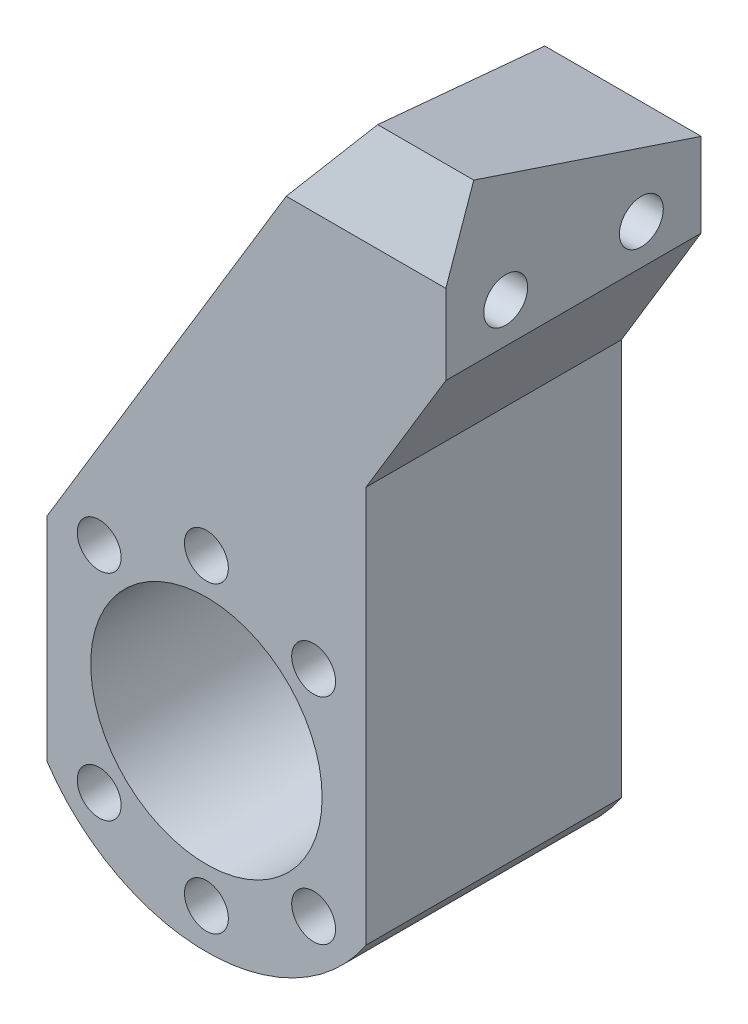
SolidWorks part; units mm, degrees
ref_plane "Plan de face" through (0, 0, 0) normal (0, 0, 1) x (1, 0, 0)
ref_plane "Plan de dessus" through (0, 0, 0) normal (0, 1, 0) x (1, 0, 0)
ref_plane "Plan de droite" through (0, 0, 0) normal (1, 0, 0) x (0, 0, -1)
sketch "Esquisse2" plane through (0, 0, 0) normal (0, 0, 1) x (1, 0, 0)
  line L0 (20, 13.2665) -> (20, -13.2665)
  line L1 (-20, 13.2665) -> (-20, -13.2665)
  line L2 (-20, 0) -> (20, 0) construction
  arc A2 (-20, 13.2665) -> (20, 13.2665) centre (0, 0) cw
  arc A3 (-20, -13.2665) -> (20, -13.2665) centre (0, 0) ccw
  circle A4 centre (0, 0) radius 19 construction
  circle A5 centre (0, 19) radius 2.75
  circle A6 centre (-13.435, 13.435) radius 2.75
  circle A7 centre (13.435, 13.435) radius 2.75
  circle A8 centre (0, -19) radius 2.75
  circle A9 centre (13.435, -13.435) radius 2.75
  circle A10 centre (-13.435, -13.435) radius 2.75
  circle A11 centre (0, 0) radius 14.5
  point P4 (0, 0)
  point P10 (-20, 0)
  point P11 (20, 0)
  dimension "D2" = 24
  dimension "D3" = 38
  dimension "D4" = 5.5
  dimension "D5" = 29
  dimension "D1" = 40
  dimension "D6" = 45
  dimension "D7" = 45
  dimension "D8" = 45
  dimension "D9" = 45
extrude "Boss.-Extru.1" add sketch "Esquisse2" along normal blind 32
sketch "Esquisse7" plane through (0, 0, 0) normal (0, 0, -1) x (-1, 0, 0)
  line L2 (-10, 63.001) -> (20, 13.2665)
  line L3 (-10, 63.001) -> (-30, 63.001)
  line L4 (-30, 63.001) -> (-30, 53.001)
  line L6 (-20, 13.2665) -> (-20, 36.4228)
  line L7 (-20, 36.4228) -> (-30, 53.001)
  arc A0 (20, 13.2665) -> (-20, 13.2665) centre (0, 0) ccw construction
  arc A1 (20, 13.2665) -> (-20, 13.2665) centre (0, 0) ccw
  dimension "D1" = 39.7345
  dimension "D2" = 10
  dimension "D3" = 10
  dimension "D4" = 20
extrude "Boss.-Extru.4" add sketch "Esquisse7" against normal up to surface (32 mm away) up to face at (0, 0, 32)
sketch "Esquisse10" plane through (30, 0, 0) normal (1, 0, 0) x (0, 0, -1)
  line L0 (-32, 53.001) -> (-32, 63.001) construction
  line L1 (-24.5, 58.001) -> (-7.5, 58.001) construction
  line L2 (-32, 63.001) -> (0, 63.001) construction
  circle A0 centre (-24.5, 58.001) radius 2.75
  circle A1 centre (-7.5, 58.001) radius 2.75
  point P4 (-16, 58.001)
  point P7 (-32, 58.001)
  point P10 (-16, 63.001)
  dimension "D1" = 5.5
  dimension "D2" = 7.5
extrude "Enlèv. mat.-Extru.3" cut sketch "Esquisse10" against normal up to next
sketch "Esquisse11" plane through (30, 0, 0) normal (1, 0, 0) x (0, 0, -1)
  line L0 (-32, 63.001) -> (0, 63.001)
  line L2 (-28.5, 73.001) -> (-32, 63.001)
  line L3 (0, 63.001) -> (0, 63.501)
  line L4 (0, 63.501) -> (-28.5, 73.001)
  dimension "D1" = 10
  dimension "D2" = 3.5
  dimension "D3" = 0.5
extrude "Boss.-Extru.6" add sketch "Esquisse11" against normal up to vertex (20 mm away)
sketch "Esquisse12" plane through (0, 0, 0) normal (0, 0, -1) x (-1, 0, 0)
  line L0 (-10, 63.001) -> (-17.9628, 73.001)
  line L2 (-10, 73.001) -> (-10, 63.001) construction
  line L3 (-10, 73.001) -> (-10, 63.001)
  line L5 (-10, 73.001) -> (-30, 73.001) construction
  line L6 (-17.9628, 73.001) -> (-10, 73.001)
extrude "Enlèv. mat.-Extru.4" cut sketch "Esquisse12" against normal up to next
ref_plane "Plan1" through (20, 0, 0) normal (1, 0, 0) x (0, 0, -1)
sketch "Esquisse13" plane through (20, 0, 0) normal (1, 0, 0) x (0, 0, -1)
  circle A0 centre (-7.5, 58.001) radius 6
  circle A1 centre (-24.5, 58.001) radius 6
  dimension "D1" = 12
extrude "Enlèv. mat.-Extru.5" cut sketch "Esquisse13" against normal up to next
